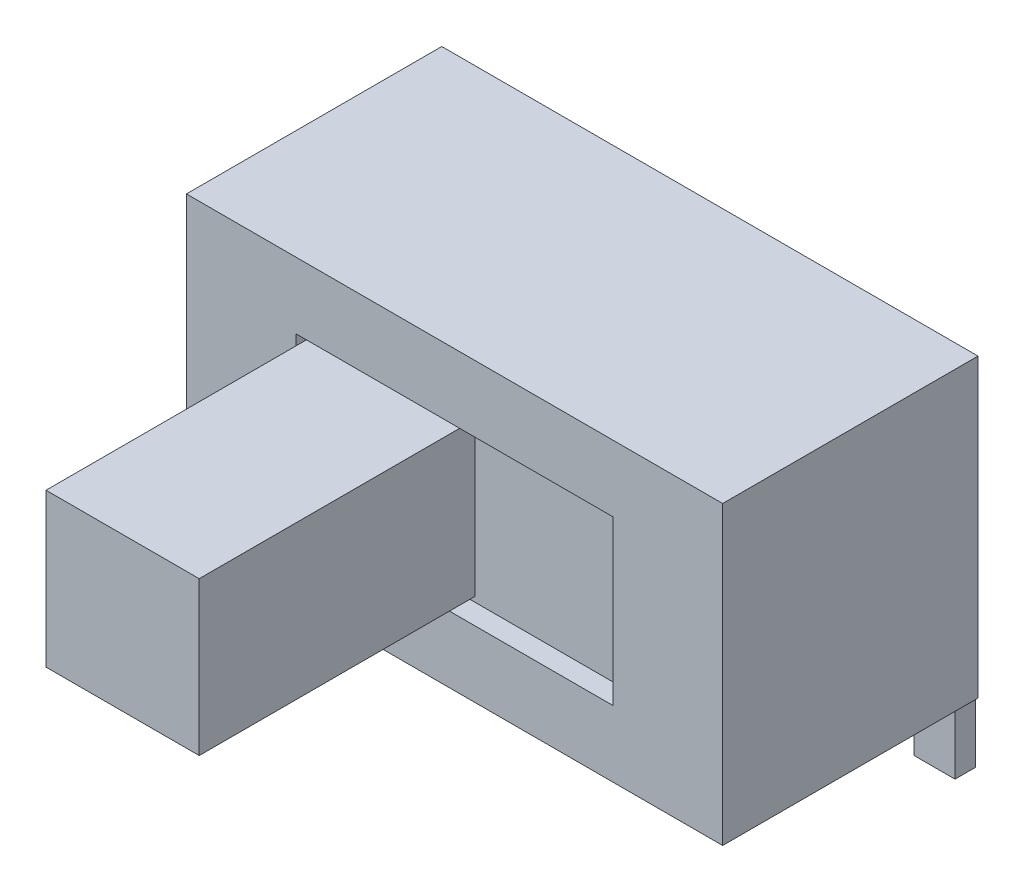
SolidWorks part; units mm, degrees
ref_plane "Front Plane" through (0, 0, 0) normal (0, 0, 1) x (1, 0, 0)
ref_plane "Top Plane" through (0, 0, 0) normal (0, 1, 0) x (1, 0, 0)
ref_plane "Right Plane" through (0, 0, 0) normal (1, 0, 0) x (0, 0, -1)
sketch "Sketch1" plane through (0, 0, 0) normal (0, 1, 0) x (1, 0, 0)
  line L1 (-5.25, 2.5) -> (5.25, 2.5)
  line L2 (-5.25, 2.5) -> (-5.25, -2.5)
  line L3 (-5.25, -2.5) -> (5.25, -2.5)
  line L4 (5.25, 2.5) -> (5.25, -2.5)
  dimension "D1" = 10.5
  dimension "D2" = 5
  dimension "D3" = 5.25
  dimension "D4" = 2.5
extrude "Boss-Extrude1" add sketch "Sketch1" along normal blind 5.8
sketch "Sketch2" plane through (0, 0, 2.5) normal (0, 0, 1) x (1, 0, 0)
  line L0 (-5.25, 5.8) -> (-5.25, 0) construction
  line L1 (-3.1, 4.5) -> (3.1, 4.5)
  line L2 (-3.1, 4.5) -> (-3.1, 1.3)
  line L3 (-3.1, 1.3) -> (3.1, 1.3)
  line L4 (3.1, 4.5) -> (3.1, 1.3)
  line L5 (-5.25, 0) -> (5.25, 0) construction
  point P6 (0, 4.5)
  point P9 (3.1, 2.9)
  dimension "D1" = 6.2
  dimension "D2" = 3.2
  dimension "D3" = 5.25
  dimension "D4" = 2.9
extrude "Cut-Extrude1" cut sketch "Sketch2" against normal blind 0.4
sketch "Sketch3" plane through (0, 0, 2.1) normal (0, 0, 1) x (1, 0, 0)
  line L0 (3.1, 4.5) -> (-3.1, 4.5) construction
  line L1 (-3, 4.4) -> (0, 4.4)
  line L2 (-3, 4.4) -> (-3, 1.4)
  line L3 (-3, 1.4) -> (0, 1.4)
  line L4 (0, 4.4) -> (0, 1.4)
  line L5 (-3.1, 4.5) -> (-3.1, 1.3) construction
  dimension "D1" = 3
  dimension "D2" = 0.1
  dimension "D3" = 0.1
extrude "Boss-Extrude2" add sketch "Sketch3" along normal offset from surface (5.4 mm away) 5 up to face at (0, 2.9, 2.5) offset beyond the face yes
sketch "Sketch4" plane through (0, 0, 0) normal (1, 0, 0) x (0, 0, -1)
  line L0 (2.5, 3.1) -> (4.3, 3.1)
  line L1 (2.5, 5.8) -> (2.5, 0) construction
  line L2 (4.3, 3.1) -> (4.3, -3)
  line L3 (4.3, -3) -> (3.9, -3)
  line L4 (3.9, -3) -> (3.9, 2.7)
  line L5 (3.9, 2.7) -> (2.5, 2.7)
  line L6 (2.5, 2.7) -> (2.5, 3.1)
  line L7 (-2.5, 5.8) -> (-2.5, 0) construction
  line L8 (2.5, 0) -> (-2.5, 0) construction
  point P12 (2.5, 2.9)
  dimension "D1" = 0.4
  dimension "D2" = 0.4
  dimension "D3" = 6.8
  dimension "D4" = 3
  dimension "D5" = 2.9
extrude "Boss-Extrude3" add sketch "Sketch4" along normal mid plane 0.8 separate body
pattern_linear "LPattern1" count 2 spacing 3 along (-1, 0, 0) count 2 spacing 3 along (1, 0, 0) of "Boss-Extrude3"
